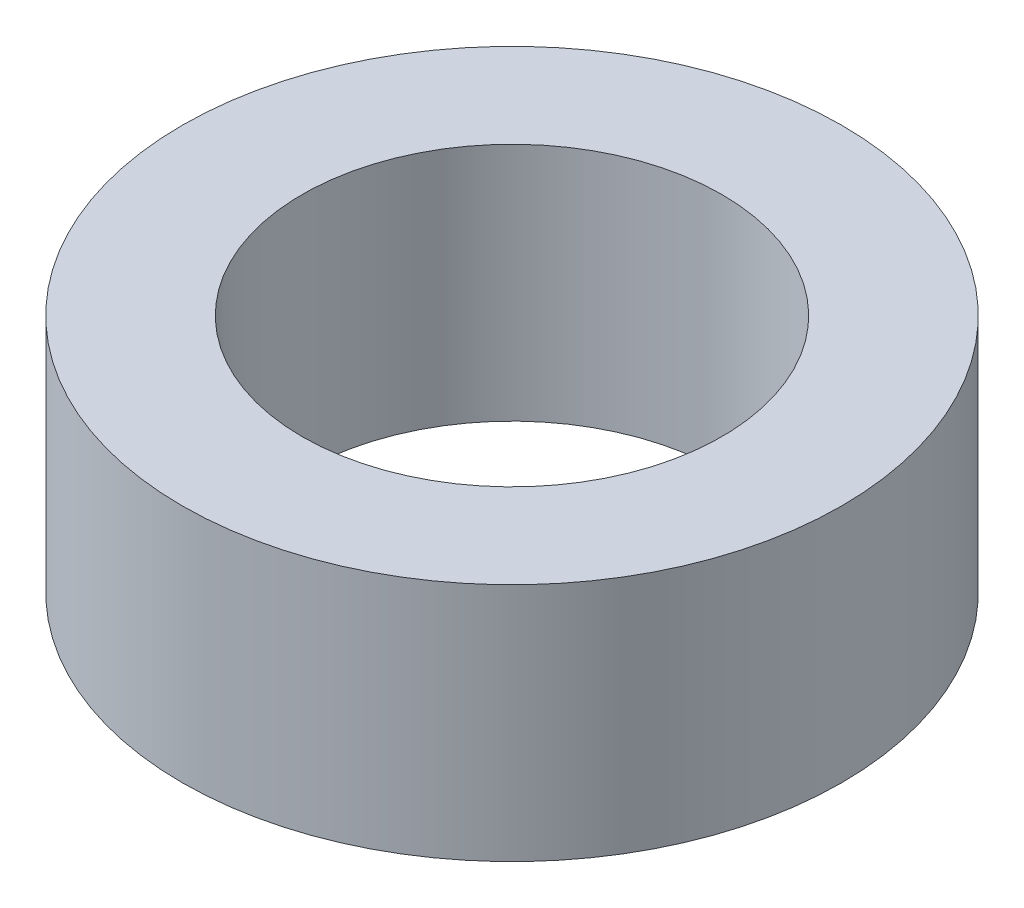
SolidWorks part; units mm, degrees
ref_plane "前视基准面" through (0, 0, 0) normal (0, 0, 1) x (1, 0, 0)
ref_plane "上视基准面" through (0, 0, 0) normal (0, 1, 0) x (1, 0, 0)
ref_plane "右视基准面" through (0, 0, 0) normal (1, 0, 0) x (0, 0, -1)
other "Configuration Table"
sketch "草图1" plane through (0, 0, 0) normal (0, 1, 0) x (1, 0, 0)
  circle A0 centre (0, 0) radius 1.75
  circle A1 centre (0, 0) radius 2.75
  dimension "D1" = 5.5
  dimension "D2" = 3.5
extrude "凸台-拉伸1" add sketch "草图1" along normal blind 2
